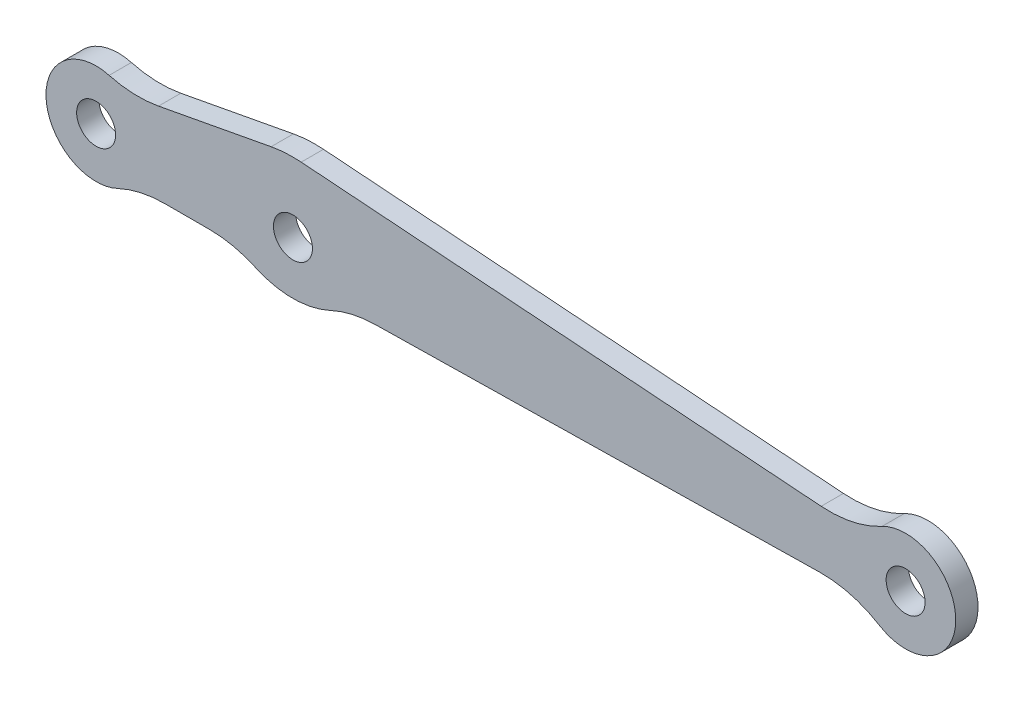
SolidWorks part; units mm, degrees
ref_plane "Front Plane" through (0, 0, 0) normal (0, 0, 1) x (1, 0, 0)
ref_plane "Top Plane" through (0, 0, 0) normal (0, 1, 0) x (1, 0, 0)
ref_plane "Right Plane" through (0, 0, 0) normal (1, 0, 0) x (0, 0, -1)
sketch "Sketch1" plane through (0, 0, 0) normal (0, 0, 1) x (1, 0, 0)
  line L0 (51.1425, -2.3172) -> (55, -2.25) construction
  line L1 (-17.67, 0) -> (0, 0) construction
  line L6 (0, 0) -> (55, 0) construction
  line L7 (0, -1.75) -> (0, -4.75) construction
  line L8 (-0.0246, 6.2498) -> (-0.0246, 1.7498) construction
  line L9 (-0.0246, 6.2498) -> (-0.0246, 1.7498) construction
  line L12 (-4.8578, -3.125) -> (4.8086, -3.125) construction
  line L15 (-17.67, 3.125) -> (-1.9592, 6.0701) construction
  line L16 (-4.8578, -3.125) -> (-17.67, -3.125) construction
  line L17 (55, 2.25) -> (0.742, 6.2218) construction
  line L19 (-1.9592, 6.0701) -> (-12.0675, 4.1752)
  line L20 (-17.67, 4.5) -> (-17.67, 1.75) construction
  line L21 (-17.67, -4.5) -> (-17.67, -1.75) construction
  line L22 (55, 2.25) -> (55, 1.75) construction
  line L23 (55, -1.75) -> (55, -2.25) construction
  line L24 (-7.4986, -3.125) -> (-11.5069, -3.125)
  line L25 (7.3756, -3.0802) -> (47.2818, -2.3846)
  line L26 (47.417, 2.8051) -> (0.742, 6.2218)
  circle A0 centre (-17.67, 0) radius 1.75
  circle A1 centre (-17.67, 0) radius 4.5 construction
  circle A2 centre (0, 0) radius 1.75
  arc A3 (52.8732, 3.9657) -> (52.6588, -3.843) centre (55, 0) cw
  arc A4 (52.8732, 3.9657) -> (47.417, 2.8051) centre (48.1471, 12.7784) cw
  arc A5 (52.6588, -3.843) -> (47.2818, -2.3846) centre (47.4561, -12.383) ccw
  arc A6 (3.3419, -4.0072) -> (7.3756, -3.0802) centre (7.55, -13.0787) cw
  arc A7 (-3.3464, -4.0278) -> (-7.4986, -3.125) centre (-7.4986, -13.125) ccw
  arc A8 (-15.7573, -4.0733) -> (-11.5069, -3.125) centre (-11.5069, -13.125) cw
  arc A9 (-12.0675, 4.1752) -> (-16.5031, 4.3461) centre (-13.91, 14.004) cw
  circle A17 centre (55, 0) radius 1.75
  circle A18 centre (55, 0) radius 4.5 construction
  circle A19 centre (-0.0246, -4.2502) radius 10.5 construction
  circle A20 centre (-0.0246, 3.25) radius 8 construction
  arc A21 (-3.3464, -4.0278) -> (3.3419, -4.0072) centre (-0.0246, 3.25) ccw
  arc A22 (-1.9592, 6.0701) -> (0.742, 6.2218) centre (-0.0246, -4.2502) cw
  arc A23 (-16.5031, 4.3461) -> (-15.7573, -4.0733) centre (-17.67, 0) ccw
  point P15 (51.2737, 2.5228)
  point P27 (-14.432, -3.125)
  point P31 (-15.0035, 3.6249)
  dimension "D3" = 4.5
  dimension "D4" = 10
  dimension "D14" = 21
  dimension "D15" = 3.5
  dimension "D16" = 9
  dimension "D17" = 9
  dimension "D18" = 3.5
  dimension "D21" = 3.5
  dimension "D22" = 16
  dimension "D19" = 17.67
  dimension "D20" = 55
  dimension "D24" = 3
  dimension "D25" = 4.5
extrude "Boss-Extrude1" add sketch "Sketch1" along normal blind 2
